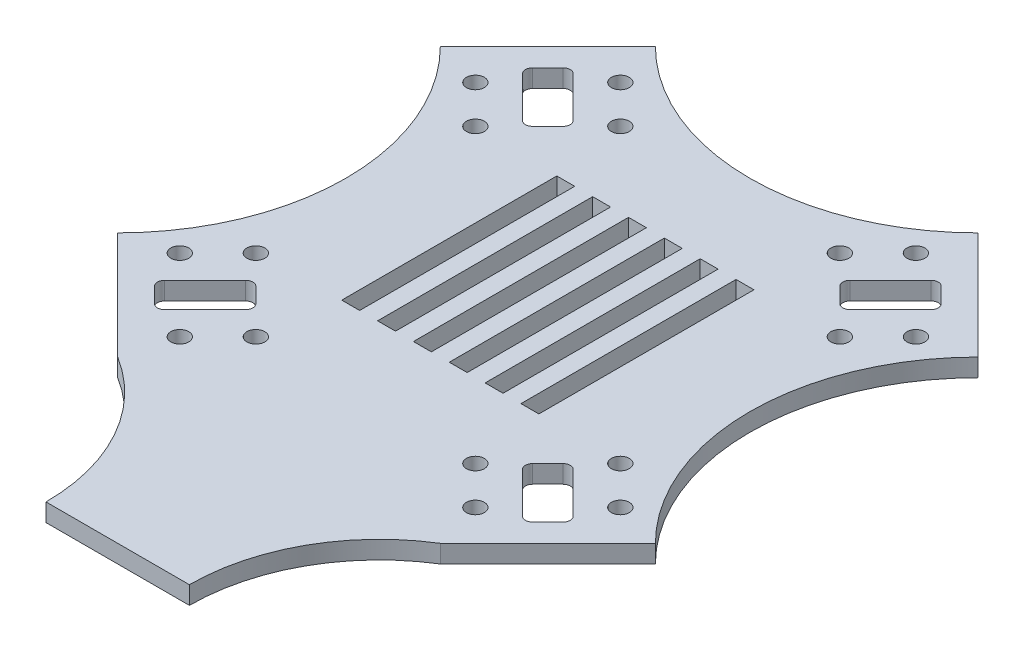
SolidWorks part; units mm, degrees
ref_plane "Front Plane" through (0, 0, 0) normal (0, 0, 1) x (1, 0, 0)
ref_plane "Top Plane" through (0, 0, 0) normal (0, 1, 0) x (1, 0, 0)
ref_plane "Right Plane" through (0, 0, 0) normal (1, 0, 0) x (0, 0, -1)
sketch "Sketch2" plane through (0, 0, 0) normal (0, 1, 0) x (1, 0, 0)
  line L0 (45, 75) -> (75, 45)
  line L5 (38.6102, 42.8529) -> (42.8529, 38.6102)
  line L6 (45.6813, 38.6102) -> (56.995, 49.924)
  line L7 (45, -75) -> (75, -45)
  line L8 (-75, -45) -> (-45, -75)
  line L9 (-75, 45) -> (-45, 75)
  line L10 (2.5, -30) -> (2.5, 30)
  line L11 (-2.5, -30) -> (-7.5, -30)
  line L12 (-2.5, -30) -> (-2.5, 30)
  line L13 (56.995, 52.7524) -> (52.7524, 56.995)
  line L14 (38.6102, 45.6813) -> (49.924, 56.995)
  line L15 (45.6813, -38.6102) -> (56.995, -49.924)
  line L16 (52.7524, -56.995) -> (56.995, -52.7524)
  line L17 (38.6102, -45.6813) -> (49.924, -56.995)
  line L18 (42.8529, -38.6102) -> (38.6102, -42.8529)
  line L19 (-38.6102, -45.6813) -> (-49.924, -56.995)
  line L20 (-56.995, -52.7524) -> (-52.7524, -56.995)
  line L21 (-45.6813, -38.6102) -> (-56.995, -49.924)
  line L22 (-38.6102, -42.8529) -> (-42.8529, -38.6102)
  line L23 (-45.6813, 38.6102) -> (-56.995, 49.924)
  line L24 (-52.7524, 56.995) -> (-56.995, 52.7524)
  line L25 (-38.6102, 45.6813) -> (-49.924, 56.995)
  line L26 (-42.8529, 38.6102) -> (-38.6102, 42.8529)
  line L27 (-2.5, 30) -> (-7.5, 30)
  line L28 (-7.5, -30) -> (-7.5, 30)
  line L29 (7.5, -30) -> (7.5, 30)
  line L30 (7.5, -30) -> (2.5, -30)
  line L31 (7.5, 30) -> (2.5, 30)
  line L32 (-17.5, -30) -> (-17.5, 30)
  line L33 (-12.5, 30) -> (-17.5, 30)
  line L34 (-12.5, -30) -> (-12.5, 30)
  line L35 (51.3382, 44.2671) -> (64.4872, 31.118) construction
  line L36 (-12.5, -30) -> (-17.5, -30)
  line L37 (-27.5, -30) -> (-27.5, 30)
  line L38 (-22.5, -30) -> (-27.5, -30)
  line L39 (-22.5, 30) -> (-27.5, 30)
  line L40 (-22.5, -30) -> (-22.5, 30)
  line L41 (12.5, -30) -> (12.5, 30)
  line L42 (17.5, -30) -> (12.5, -30)
  line L43 (17.5, -30) -> (17.5, 30)
  line L44 (17.5, 30) -> (12.5, 30)
  line L45 (22.5, -30) -> (22.5, 30)
  line L46 (27.5, -30) -> (22.5, -30)
  line L47 (27.5, -30) -> (27.5, 30)
  line L48 (27.5, 30) -> (22.5, 30)
  line L49 (57.9127, 37.6926) -> (50.8416, 30.6215) construction
  line L50 (57.9127, 37.6926) -> (61.4482, 41.2281) construction
  line L51 (40.7316, 40.7316) -> (54.8737, 54.8737) construction
  arc A0 (-45, 75) -> (45, 75) centre (0, 120) ccw
  arc A1 (-75, 45) -> (-75, -45) centre (-120, 0) cw
  arc A2 (75, 45) -> (75, -45) centre (120, 0) ccw
  arc A3 (-45, -75) -> (45, -75) centre (0, -120) cw
  arc A13 (42.8529, 38.6102) -> (45.6813, 38.6102) centre (44.2671, 40.0245) ccw
  arc A14 (56.995, 49.924) -> (56.995, 52.7524) centre (55.5808, 51.3382) ccw
  arc A15 (38.6102, 42.8529) -> (38.6102, 45.6813) centre (40.0245, 44.2671) cw
  arc A16 (49.924, 56.995) -> (52.7524, 56.995) centre (51.3382, 55.5808) cw
  arc A17 (56.995, -49.924) -> (56.995, -52.7524) centre (55.5808, -51.3382) cw
  arc A18 (49.924, -56.995) -> (52.7524, -56.995) centre (51.3382, -55.5808) ccw
  arc A19 (38.6102, -42.8529) -> (38.6102, -45.6813) centre (40.0245, -44.2671) ccw
  arc A20 (42.8529, -38.6102) -> (45.6813, -38.6102) centre (44.2671, -40.0245) cw
  arc A21 (-49.924, -56.995) -> (-52.7524, -56.995) centre (-51.3382, -55.5808) cw
  arc A22 (-56.995, -49.924) -> (-56.995, -52.7524) centre (-55.5808, -51.3382) ccw
  arc A23 (-42.8529, -38.6102) -> (-45.6813, -38.6102) centre (-44.2671, -40.0245) ccw
  arc A24 (-38.6102, -42.8529) -> (-38.6102, -45.6813) centre (-40.0245, -44.2671) cw
  arc A25 (-56.995, 49.924) -> (-56.995, 52.7524) centre (-55.5808, 51.3382) cw
  arc A26 (-49.924, 56.995) -> (-52.7524, 56.995) centre (-51.3382, 55.5808) ccw
  arc A27 (-38.6102, 42.8529) -> (-38.6102, 45.6813) centre (-40.0245, 44.2671) ccw
  arc A28 (-42.8529, 38.6102) -> (-45.6813, 38.6102) centre (-44.2671, 40.0245) cw
  circle A29 centre (50.8416, 30.6215) radius 2.5
  circle A31 centre (61.4482, 41.2281) radius 2.5
  circle A32 centre (30.6215, 50.8416) radius 2.5
  circle A33 centre (41.2281, 61.4482) radius 2.5
  circle A34 centre (30.6215, -50.8416) radius 2.5
  circle A35 centre (41.2281, -61.4482) radius 2.5
  circle A36 centre (61.4482, -41.2281) radius 2.5
  circle A37 centre (50.8416, -30.6215) radius 2.5
  circle A38 centre (-50.8416, -30.6215) radius 2.5
  circle A39 centre (-61.4482, -41.2281) radius 2.5
  circle A40 centre (-41.2281, -61.4482) radius 2.5
  circle A41 centre (-30.6215, -50.8416) radius 2.5
  circle A42 centre (-30.6215, 50.8416) radius 2.5
  circle A43 centre (-41.2281, 61.4482) radius 2.5
  circle A44 centre (-61.4482, 41.2281) radius 2.5
  circle A45 centre (-50.8416, 30.6215) radius 2.5
  point P0 (0, 0)
  point P22 (-2.5, 0)
  point P35 (0, 0)
  point P42 (44.2671, 37.196)
  point P45 (58.4092, 51.3382)
  point P50 (40.7316, 40.7316)
  point P52 (54.8737, 54.8737)
  point P89 (0, 0)
  point P127 (0, 0)
  point P134 (0, 0)
  dimension "D2" = 5
  dimension "D1" = 60
  dimension "D6" = 2
  dimension "D10" = 5
  dimension "D11" = 5
  dimension "D15" = 5
  dimension "D16" = 5
  dimension "D4" = 5
  dimension "D5" = 20
  dimension "D8" = 5
  dimension "D9" = 5
  dimension "D3" = 5
  dimension "D12" = 2.5
  dimension "D13" = 10
  dimension "D14" = 5
  dimension "D7" = 4
extrude "Boss-Extrude1" add sketch "Sketch2" against normal blind 5
sketch "Sketch3" plane through (0, 0, 0) normal (0, 1, 0) x (1, 0, 0)
  line L2 (-20, -120) -> (20, -120)
  arc A0 (-45, -75) -> (45, -75) centre (0, -120) cw
  arc A1 (20, -120) -> (45, -75) centre (73, -120) cw
  arc A2 (-20, -120) -> (-45, -75) centre (-73, -120) ccw
  dimension "D1" = 20
extrude "Boss-Extrude2" add sketch "Sketch3" against normal blind 5
